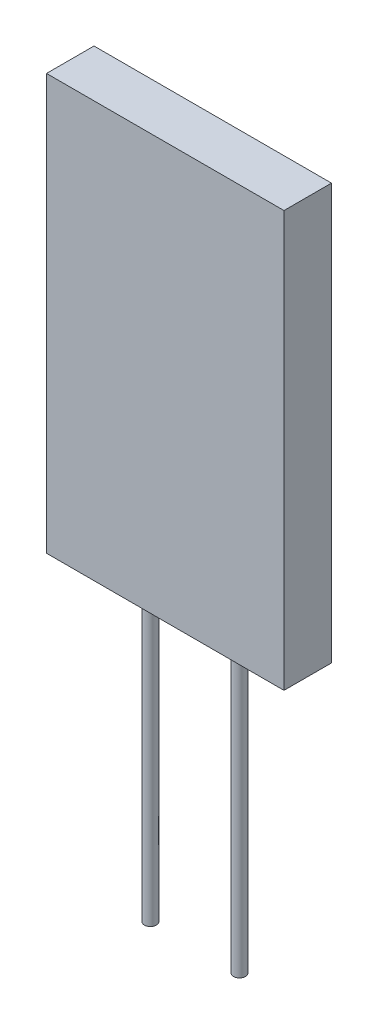
SolidWorks part; units mm, degrees
ref_plane "前视基准面" through (0, 0, 0) normal (0, 0, 1) x (1, 0, 0)
ref_plane "上视基准面" through (0, 0, 0) normal (0, 1, 0) x (1, 0, 0)
ref_plane "右视基准面" through (0, 0, 0) normal (1, 0, 0) x (0, 0, -1)
sketch "草图1" plane through (0, 0, 0) normal (0, 0, 1) x (1, 0, 0)
  line L1 (-2, -3.5) -> (2, -3.5)
  line L2 (-2, -3.5) -> (-2, 3.5)
  line L3 (-2, 3.5) -> (2, 3.5)
  line L4 (2, -3.5) -> (2, 3.5)
  line L5 (-2, -3.5) -> (2, 3.5) construction
  line L6 (-2, 3.5) -> (2, -3.5) construction
  point P0 (0, 0)
  dimension "D1" = 4
  dimension "D2" = 7
extrude "凸台-拉伸1" add sketch "草图1" along normal blind 1
sketch "草图2" plane through (0, 0, 0) normal (0, 0, 1) x (1, 0, 0)
  line L0 (1.5, 3.5) -> (1.5, -3.5)
  line L1 (2, 3.5) -> (-2, 3.5) construction
  line L2 (-2, -3.5) -> (2, -3.5) construction
  line L3 (1, 3.5) -> (1, -3.5)
  line L4 (0.5, 3.5) -> (0.5, -3.5)
  line L5 (0, 3.5) -> (0, -3.5)
  line L6 (-0.5, 3.5) -> (-0.5, -3.5)
  line L7 (-1, 3.5) -> (-1, -3.5)
  line L8 (-1.5, 3.5) -> (-1.5, -3.5)
  line L10 (2, 3.5) -> (2, -3.5)
  line L11 (2, -3.5) -> (1.5, -3.5)
  line L12 (1, -3.5) -> (0.5, -3.5)
  line L13 (0, -3.5) -> (-0.5, -3.5)
  line L14 (-1, -3.5) -> (-1.5, -3.5)
  line L15 (-1, 3.5) -> (-1.5, 3.5)
  line L16 (0, 3.5) -> (-0.5, 3.5)
  line L17 (1, 3.5) -> (0.5, 3.5)
  line L18 (2, 3.5) -> (1.5, 3.5)
  line L20 (-2, 3.5) -> (-2, -3.5) [skipped]
  dimension "D1" = 0.5
  dimension "D2" = 8
extrude "切除-拉伸2" cut sketch "草图2" along normal blind 0.2
sketch "草图3" plane through (0, 0, 0) normal (0, 0, 1) x (1, 0, 0)
  line L0 (2, 3.5) -> (-2, 3.5)
  line L1 (2, 3.0455) -> (-2, 3.0455)
  line L2 (2, 2.591) -> (-2, 2.591)
  line L3 (2, 2.1365) -> (-2, 2.1365)
  line L4 (2, 1.6819) -> (-2, 1.6819)
  line L5 (2, 1.2274) -> (-2, 1.2274)
  line L6 (2, 0.7729) -> (-2, 0.7729)
  line L7 (2, 0.3184) -> (-2, 0.3184)
  line L8 (2, -0.1361) -> (-2, -0.1361)
  line L9 (2, -0.5906) -> (-2, -0.5906)
  line L10 (2, -1.0452) -> (-2, -1.0452)
  line L11 (2, -1.4997) -> (-2, -1.4997)
  line L12 (2, -1.9542) -> (-2, -1.9542)
  line L13 (2, -2.4087) -> (-2, -2.4087)
  line L14 (2, -2.8632) -> (-2, -2.8632)
  line L15 (2, -3.3177) -> (-2, -3.3177)
  line L17 (2, 3.5) -> (2, 3.0455)
  line L18 (-2, 3.5) -> (-2, 3.0455)
  line L19 (2, 2.591) -> (2, 2.1365)
  line L20 (-2, 2.591) -> (-2, 2.1365)
  line L21 (2, 1.6819) -> (2, 1.2274)
  line L22 (-2, 1.6819) -> (-2, 1.2274)
  line L23 (2, 0.7729) -> (2, 0.3184)
  line L24 (-2, 0.7729) -> (-2, 0.3184)
  line L25 (2, -0.1361) -> (2, -0.5906)
  line L26 (-2, -0.1361) -> (-2, -0.5906)
  line L27 (2, -1.0452) -> (2, -1.4997)
  line L28 (-2, -1.0452) -> (-2, -1.4997)
  line L29 (2, -1.9542) -> (2, -2.4087)
  line L30 (-2, -1.9542) -> (-2, -2.4087)
  line L31 (2, -2.8632) -> (2, -3.3177)
  line L32 (-2, -2.8632) -> (-2, -3.3177)
  line L33 (2, -3.7723) -> (-2, -3.7723) [skipped]
  dimension "D1" = 17
extrude "切除-拉伸4" cut sketch "草图3" along normal blind 0.2
ref_plane "基准面4" through (0, 0, 0.5) normal (0, 0, 1) x (1, 0, 0)
sketch "草图4" plane through (0, 0, 0.5) normal (0, 0, 1) x (1, 0, 0)
  line L0 (-0.75, -3.5) -> (-0.75, -8.5)
  line L1 (-1, -3.5) -> (-0.5, -3.5) construction
  dimension "D1" = 5
sweep "扫描1" add path "草图4" circular profile diameter 0.2 parameters "D3"=0.2
sketch "草图11" plane through (0, 0, 0.5) normal (0, 0, 1) x (1, 0, 0)
  line L0 (0.75, -3.5) -> (0.75, -8.5)
  line L2 (0.5, -3.5) -> (1, -3.5) construction
  dimension "D1" = 5
sweep "扫描2" add path "草图11" circular profile diameter 0.2 parameters "D3"=0.2
